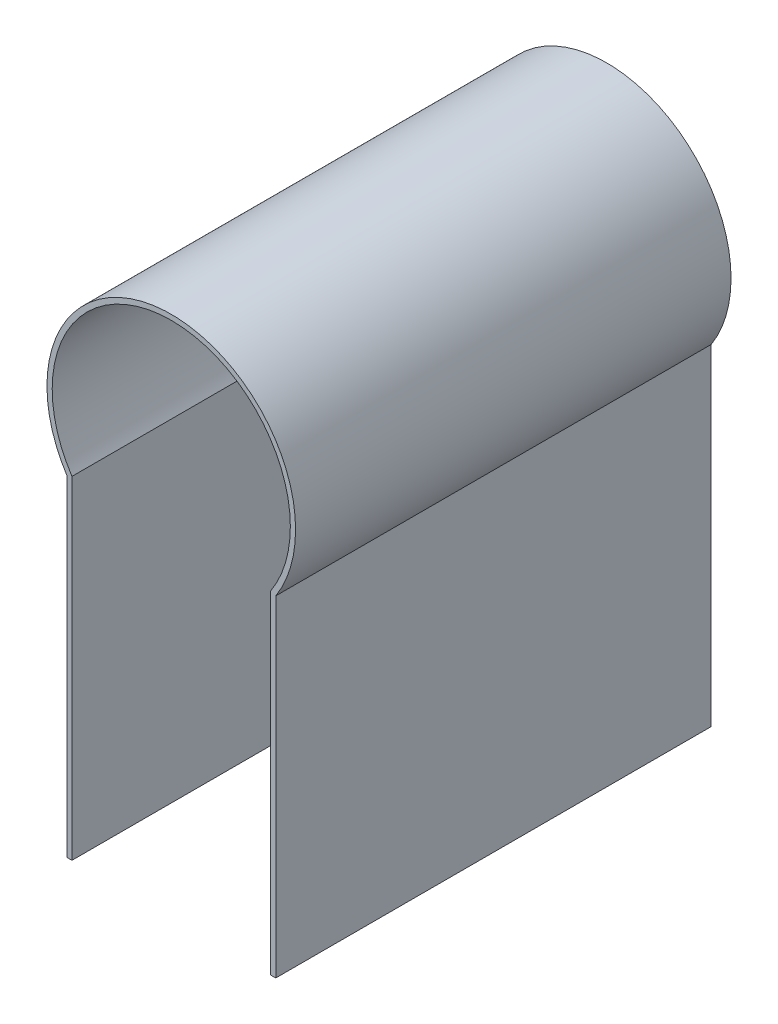
SolidWorks part; units mm, degrees
ref_plane "Alzado" through (0, 0, 0) normal (0, 0, 1) x (1, 0, 0)
ref_plane "Planta" through (0, 0, 0) normal (0, 1, 0) x (1, 0, 0)
ref_plane "Vista lateral" through (0, 0, 0) normal (1, 0, 0) x (0, 0, -1)
sketch "Croquis1" plane through (0, 0, 0) normal (0, 0, 1) x (1, 0, 0)
  line L0 (0, 0) -> (0, 300) construction
  line L1 (-60, 0) -> (60, 0) construction
  line L2 (0, 0) -> (0, 190) construction
  line L3 (60, 0) -> (60, 190)
  line L4 (0, 190) -> (0, 300) construction
  line L5 (0, 300) -> (0, 245) construction
  line L6 (-60, 0) -> (-60, 190)
  line L7 (-57, 0) -> (-57, 190.8927)
  line L8 (57, 0) -> (57, 190.8927)
  line L9 (-60, 0) -> (-57, 0)
  line L10 (57, 0) -> (60, 0)
  arc A0 (-60, 190) -> (60, 190) centre (0, 228.6364) cw
  arc A1 (-57, 190.8927) -> (57, 190.8927) centre (0, 228.6364) cw
  dimension "D1" = 3
  dimension "D2" = 60
  dimension "D3" = 190
extrude "Saliente-Extruir1" add sketch "Croquis1" along normal blind 250
